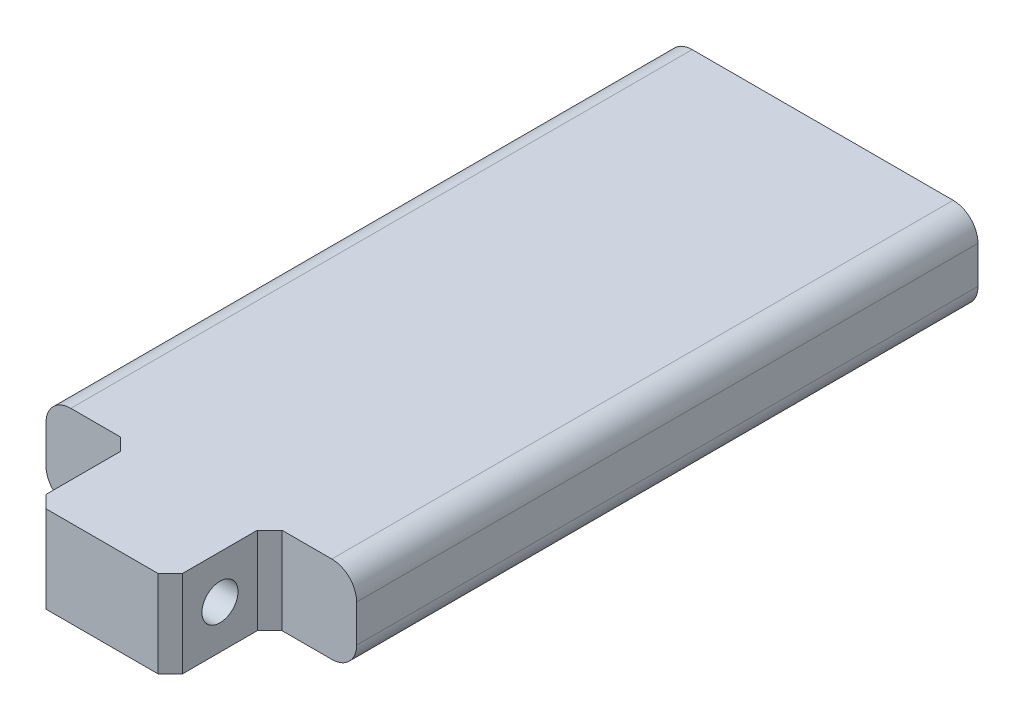
SolidWorks part; units mm, degrees
material "AISI 1020"
ref_plane "Front Plane" through (0, 0, 0) normal (0, 0, 1) x (1, 0, 0)
ref_plane "Top Plane" through (0, 0, 0) normal (0, 1, 0) x (1, 0, 0)
ref_plane "Right Plane" through (0, 0, 0) normal (1, 0, 0) x (0, 0, -1)
sketch "Sketch1" plane through (0, 0, 0) normal (0, 0, 1) x (1, 0, 0)
  line L1 (-12.5, -3.5) -> (12.5, -3.5)
  line L2 (-12.5, -3.5) -> (-12.5, 3.5)
  line L3 (-12.5, 3.5) -> (12.5, 3.5)
  line L4 (12.5, -3.5) -> (12.5, 3.5)
  line L5 (-12.5, -3.5) -> (12.5, 3.5) construction
  line L6 (-12.5, 3.5) -> (12.5, -3.5) construction
  point P0 (0, 0)
  dimension "D1" = 25
  dimension "D2" = 7
extrude "Boss-Extrude1" add sketch "Sketch1" along normal blind 58
sketch "Sketch2" plane through (0, 3.5, 0) normal (0, 1, 0) x (1, 0, 0)
  line L2 (-12.5, -58) -> (-5.5, -58)
  line L4 (-12.5, -58) -> (-12.5, -50)
  line L5 (-12.5, -50) -> (-5.5, -50)
  line L6 (-5.5, -58) -> (-5.5, -50)
  line L7 (12.5, -58) -> (5.5, -58)
  line L8 (12.5, -58) -> (12.5, -50)
  line L9 (12.5, -50) -> (5.5, -50)
  line L10 (5.5, -58) -> (5.5, -50)
  dimension "D1" = 8
  dimension "D2" = 7
extrude "Cut-Extrude1" cut sketch "Sketch2" against normal through all
hole_wizard "M3x0.5 Tapped Hole2" positions "Sketch5" profile "Sketch6" tap size "M3x0.5" standard "ANSI Metric"
sketch "Sketch5" plane through (0, 0, 0) normal (0, 0, -1) x (-1, 0, 0)
  line L0 (-12.5, 3.5) -> (12.5, 3.5) construction
  point P0 (-7, 0)
  point P2 (7, 0)
  dimension "D1" = 7
  dimension "D2" = 7
  dimension "D3" = 3.5
  dimension "D4" = 3.5
sketch "Sketch6" plane through (7, 0, 0) normal (1, 0, 0) x (0, 1, 0)
  line L0 (0, 0) -> (0, 8.4013)
  line L1 (0, 8.4013) -> (1.5, 7.5)
  line L2 (1.5, 7.5) -> (1.5, 0)
  line L5 (1.5, 0) -> (0, 0)
  line L10 (0, 8.4013) -> (-1.5, 7.5) construction
  line L11 (0, -6.35) -> (0, 107.95) construction
  dimension "Tap Drill Dia." = 3
  dimension "Tap Drill Depth" = 7.5
  dimension "Drill Angle" = 118
cosmetic thread "Hole Thread3" parameters "D1"=6, "D2"=3
cosmetic thread "Hole Thread4" parameters "D1"=6, "D2"=3
chamfer "Chamfer1" distance 1 angle 45 2 edges at (5.5, 0, 58) (-5.5, 0, 58)
hole_wizard "M2.5 Clearance Hole1" positions "Sketch7" profile "Sketch8" hole size "M2.5" standard "ANSI Metric" end condition through all
sketch "Sketch7" plane through (-5.5, -6.575, -1.7065) normal (-1, 0, 0) x (0, 0, 1)
  point P0 (55.7065, 6.575)
sketch "Sketch8" plane through (-5.5, 0, 54) normal (0, 1, 0) x (0, 0, 1)
  line L0 (0, 0) -> (0, 18)
  line L1 (0, 18) -> (1.45, 18)
  line L2 (1.45, 18) -> (1.45, 0)
  line L5 (1.45, 0) -> (0, 0)
  line L11 (0, -6.35) -> (0, 107.95) construction
  dimension "Thru Hole Dia." = 2.9
  dimension "Thru Hole Depth" = 18
fillet "Fillet1" radius 2 4 edges at (12.5, 3.5, 25) (12.5, -3.5, 25) (-12.5, 3.5, 25) (-12.5, -3.5, 25)
chamfer "Chamfer2" distance 1 angle 45 2 edges at (5.5, 0, 50) (-5.5, 0, 50)
